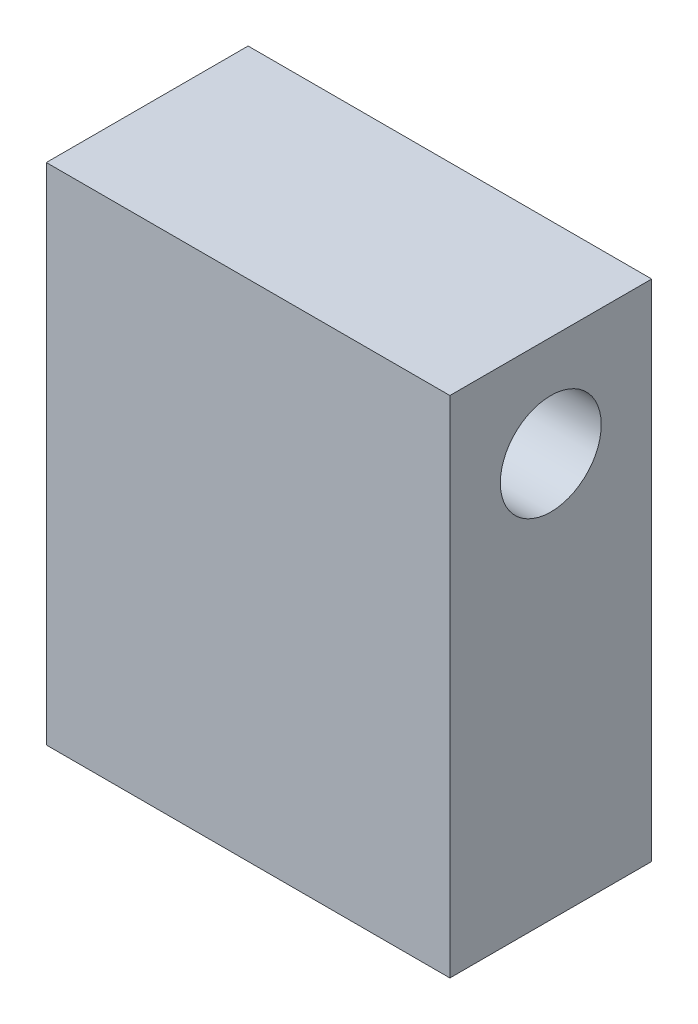
SolidWorks part; units mm, degrees
material "Perspex (TM) GS Acrylic Cast Sheet"
ref_plane "Front Plane" through (0, 0, 0) normal (0, 0, 1) x (1, 0, 0)
ref_plane "Top Plane" through (0, 0, 0) normal (0, 1, 0) x (1, 0, 0)
ref_plane "Right Plane" through (0, 0, 0) normal (1, 0, 0) x (0, 0, -1)
sketch "Sketch1" plane through (0, 0, 0) normal (0, 1, 0) x (1, 0, 0)
  line L1 (-10, 5) -> (10, 5)
  line L2 (-10, 5) -> (-10, -5)
  line L3 (-10, -5) -> (10, -5)
  line L4 (10, 5) -> (10, -5)
  line L5 (-10, 5) -> (10, -5) construction
  line L6 (-10, -5) -> (10, 5) construction
  point P0 (0, 0)
  dimension "D1" = 10
  dimension "D2" = 20
extrude "Boss-Extrude1" add sketch "Sketch1" along normal blind 25
sketch "Sketch2" plane through (0, 0, 0) normal (0, 1, 0) x (1, 0, 0)
  line L0 (-11, 0) -> (11, 0) construction
  line L1 (-10, 5) -> (-10, -5) construction
  line L2 (10, -5) -> (10, 5) construction
  circle A0 centre (-5, 0) radius 1.5
  circle A1 centre (5, 0) radius 1.5
  dimension "D1" = 3
  dimension "D3" = 5
  dimension "D2" = 5
extrude "Cut-Extrude1" cut sketch "Sketch2" along normal blind 10
sketch "Sketch3" plane through (0, 0, 0) normal (1, 0, 0) x (0, 0, -1)
  line L0 (0, 11) -> (0, -11) construction
  line L1 (-5, 25) -> (5, 25) construction
  circle A0 centre (0, 20) radius 2.5
  dimension "D2" = 5
  dimension "D1" = 5
extrude "Cut-Extrude2" cut sketch "Sketch3" against normal mid plane 40
